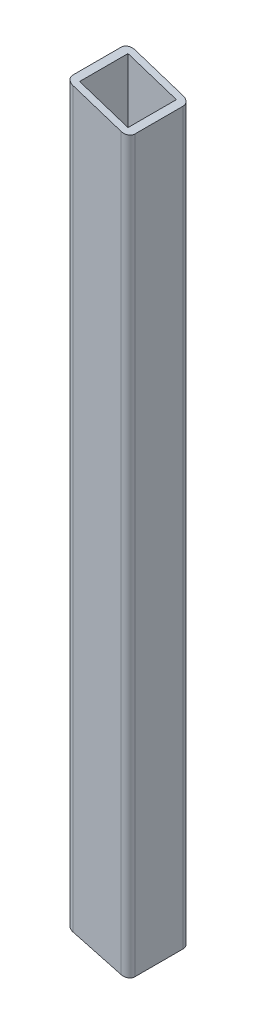
SolidWorks part; units mm, degrees
ref_plane "Front Plane" through (0, 0, 0) normal (0, 0, 1) x (1, 0, 0)
ref_plane "Top Plane" through (0, 0, 0) normal (0, 1, 0) x (1, 0, 0)
ref_plane "Right Plane" through (0, 0, 0) normal (1, 0, 0) x (0, 0, -1)
sketch "Sketch1" plane through (0, 0, 0) normal (0, 1, 0) x (1, 0, 0)
  line L1 (2.8, 0) -> (22.8, 0)
  line L2 (0, -2.8) -> (0, -22.8)
  line L3 (2.8, -25.6) -> (22.8, -25.6)
  line L4 (25.6, -2.8) -> (25.6, -22.8)
  arc A0 (22.8, 0) -> (25.6, -2.8) centre (22.8, -2.8) cw
  arc A1 (22.8, -25.6) -> (25.6, -22.8) centre (22.8, -22.8) ccw
  arc A2 (0, -22.8) -> (2.8, -25.6) centre (2.8, -22.8) ccw
  arc A3 (2.8, 0) -> (0, -2.8) centre (2.8, -2.8) ccw
  point P7 (25.6, 0)
  point P10 (25.6, -25.6)
  point P15 (0, 0)
  dimension "D2" = 2.8
  dimension "D1" = 25.6
extrude "Boss-Extrude1" add sketch "Sketch1" along normal blind 310
sketch "Sketch3" plane through (0, 0, 0) normal (0, -1, 0) x (-1, 0, 0)
  line L4 (-2.8, -2.8) -> (-22.8, -2.8)
  line L5 (-2.8, -2.8) -> (-2.8, -22.8)
  line L6 (-2.8, -22.8) -> (-22.8, -22.8)
  line L7 (-22.8, -2.8) -> (-22.8, -22.8)
  line L8 (-2.8, -2.8) -> (-22.8, -22.8) construction
  line L9 (-2.8, -22.8) -> (-22.8, -2.8) construction
  point P6 (-12.8, -12.8)
extrude "Cut-Extrude1" cut sketch "Sketch3" against normal blind 1040.5
ref_plane "Plane1" through (0, 0, 22.8) normal (0, 0, 1) x (1, 0, 0)
sketch "Sketch4" plane through (0, 0, 22.8) normal (0, 0, 1) x (1, 0, 0)
  line L0 (0, 310) -> (25.6, 301.6821)
  line L1 (25.6, 310) -> (25.6, 0) construction
extrude "Cut-Extrude2" cut sketch "Sketch4" against normal through all and the other way through all
sketch "Sketch5" plane through (0, 0, 22.8) normal (0, 0, 1) x (1, 0, 0)
  line L0 (25.6, 0) -> (0, 6.8595)
  line L1 (0, 310) -> (0, 0) construction
extrude "Cut-Extrude3" cut sketch "Sketch5" against normal through all and the other way through all
